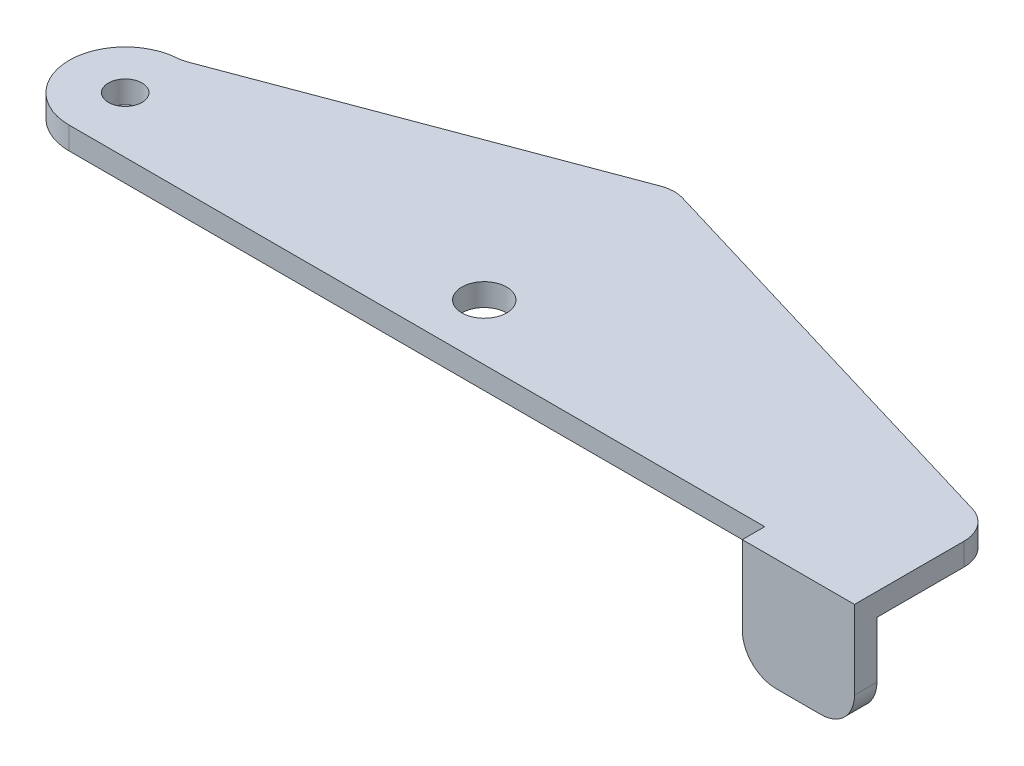
SolidWorks part; units mm, degrees
ref_plane "前视基准面" through (0, 0, 0) normal (0, 0, 1) x (1, 0, 0)
ref_plane "上视基准面" through (0, 0, 0) normal (0, 1, 0) x (1, 0, 0)
ref_plane "右视基准面" through (0, 0, 0) normal (1, 0, 0) x (0, 0, -1)
sketch "草图1" plane through (0, 0, 0) normal (0, 1, 0) x (1, 0, 0)
  line L0 (0, 55.5263) -> (0, -49.4908) construction
  line L1 (-51.7038, 0) -> (93.1474, 0) construction
  line L4 (-32, 5) -> (0, 17)
  line L5 (40, -5) -> (-32, -5)
  line L6 (0, 17) -> (40, 5)
  line L9 (40, 5) -> (40, -5)
  arc A0 (-32, 5) -> (-32, -5) centre (-32, 0) ccw
  circle A1 centre (-32, 0) radius 1.5
  circle A2 centre (0, 0) radius 2
  dimension "D3" = 3
  dimension "D7" = 4
  dimension "D4" = 17
  dimension "D1" = 10
  dimension "D2" = 32
  dimension "D5" = 5
  dimension "D6" = 40
  dimension "D8" = 10
extrude "凸台-拉伸1" add sketch "草图1" along normal blind 2
sketch "草图2" plane through (0, 2, 0) normal (0, 1, 0) x (1, 0, 0)
  line L0 (40, -5) -> (30, -5)
  line L1 (40, -5) -> (40, -7)
  line L2 (30, -5) -> (30, -7)
  line L3 (40, -7) -> (30, -7)
  line L5 (-32, -5) -> (40, -5) construction
  line L6 (40, -5) -> (40, 5) construction
  dimension "D1" = 2
  dimension "D2" = 10
extrude "凸台-拉伸2" add sketch "草图2" against normal blind 10
fillet "圆角1" radius 3 3 edges at (-32, 1, -5) (40, 1, -5) (0, 1, -17)
fillet "圆角2" radius 3 2 edges at (40, -8, 6) (30, -8, 6)
